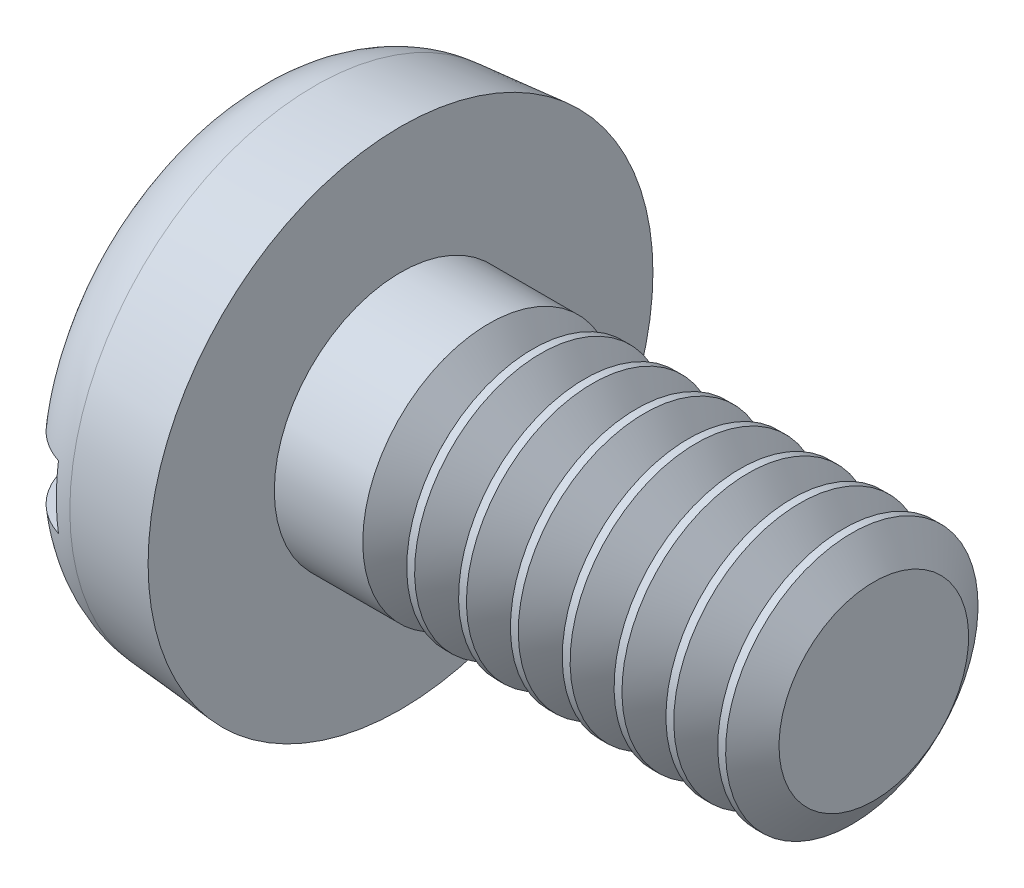
SolidWorks part; units mm, degrees
ref_plane "Plane1" through (0, 0, 0) normal (0, 0, 1) x (1, 0, 0)
ref_plane "Plane2" through (0, 0, 0) normal (0, 1, 0) x (1, 0, 0)
ref_plane "Plane3" through (0, 0, 0) normal (1, 0, 0) x (0, 0, -1)
sketch "BodySke" plane through (0, 0, 0) normal (0, 0, 1) x (1, 0, 0)
  line L0 (1, 0.8) -> (1, 1.6)
  line L1 (0, 0) -> (0, 1.5125)
  line L2 (-25.4, 0) -> (127, 0) construction
  line L3 (4, 0) -> (0, 0)
  line L4 (1, 0.8) -> (4, 0.8)
  line L5 (4, 0.8) -> (4, 0)
  line L6 (0, 1.5125) -> (1, 1.6)
  line L9 (1.35, 2.3875) -> (1.35, -7.1375) construction
  line L10 (0, 6.35) -> (0, -3.175) construction
  dimension "Head_ht" = 1
  dimension "Diameter" = 1.6
  dimension "Length" = 3
  dimension "Head_dia" = 3.2
  dimension "Advance" = 0.35
  dimension "Thread_nom" = 4
  dimension "Head_side_angle" = 5
revolve "Base-Revolve" add sketch "BodySke"
cosmetic thread "ThreadCosmetic" [suppressed]
fillet "Fillet1" [suppressed] radius 0.1
fillet "Fillet2" radius 0.5 1 edges at (0, 0, 1.5125)
sketch "Sketch2" plane through (0, 0, 0) normal (1, 0, 0) x (0, 0, -1)
  line L0 (1.6, -0.2) -> (-1.6, -0.2)
  line L1 (1.6, -0.2) -> (1.6, 0.2)
  line L2 (-1.6, 0.2) -> (1.6, 0.2)
  line L3 (-1.6, 0.2) -> (-1.6, -0.2)
  dimension "D1" = 3.2
  dimension "D2" = 1.6
  dimension "Slot_width" = 0.4
  dimension "D3" = 0.2
extrude "Slot" cut sketch "Sketch2" along normal blind 0.35
sketch "ThdSchSke" plane through (0, 0, 0) normal (0, 0, 1) x (1, 0, 0)
  line L0 (1.7, -0.601) -> (1.5607, -0.8)
  line L1 (1.7, -0.601) -> (1.8393, -0.8)
  line L2 (1.8393, -0.8) -> (1.8393, -1)
  line L3 (-3.175, 0) -> (5.1513, 0) construction
  line L5 (1.8393, -1) -> (1.5607, -1)
  line L6 (1.5607, -1) -> (1.5607, -0.8)
  dimension "Thread_minor" = 1.202
  dimension "Diameter" = 1.6
  dimension "Start" = 1.7
  dimension "SideAngle" = 55
  dimension "VeeAngle" = 70
  dimension "Overcut" = 2
revolve "ThreadSchematic" cut sketch "ThdSchSke" angle 360 about L3
pattern_linear "ThdSchPat" count 8 spacing 0.3286 along (1, 0, 0) of "ThreadSchematic"
equation "\"D1@Sketch2\" = \"Head_dia@BodySke\""
equation "\"D2@Sketch2\" = \"D1@Sketch2\" / 2"
equation "\"D3@Sketch2\" = \"Slot_width@Sketch2\" / 2"
equation "\"Thread_length@ThreadCosmetic\" = ((sgn( (\"Length@BodySke\" - \"Advance@BodySke\" * 2.0 ) - \"Thread_nom@BodySke\" )-1)*( (\"Length@BodySke\" - \"Advance@BodySke\"  * 2.0) - \"Thread_nom@BodySke\" ))/-2+ \"Thread_nom@BodySke\""
equation "\"Thread_minor@ThdSchSke\" = \"Thread_minor@ThreadCosmetic\""
equation "\"Diameter@ThdSchSke\" = \"Diameter@BodySke\""
equation "\"Overcut@ThdSchSke\" = \"Diameter@BodySke\" * 1.25"
equation "\"Start@ThdSchSke\" = \"Head_ht@BodySke\" + \"Length@BodySke\" - \"Thread_length@ThreadCosmetic\"  '---Non-countersunk---"
equation "\"Num_threads@ThdSchPat\" = int( \"Thread_length@ThreadCosmetic\" / \"Advance@BodySke\" + 0.999 )  + 1"
equation "\"Advance@ThdSchPat\" = \"Thread_length@ThreadCosmetic\" /  (\"Num_threads@ThdSchPat\" - 1) 'relax it"
